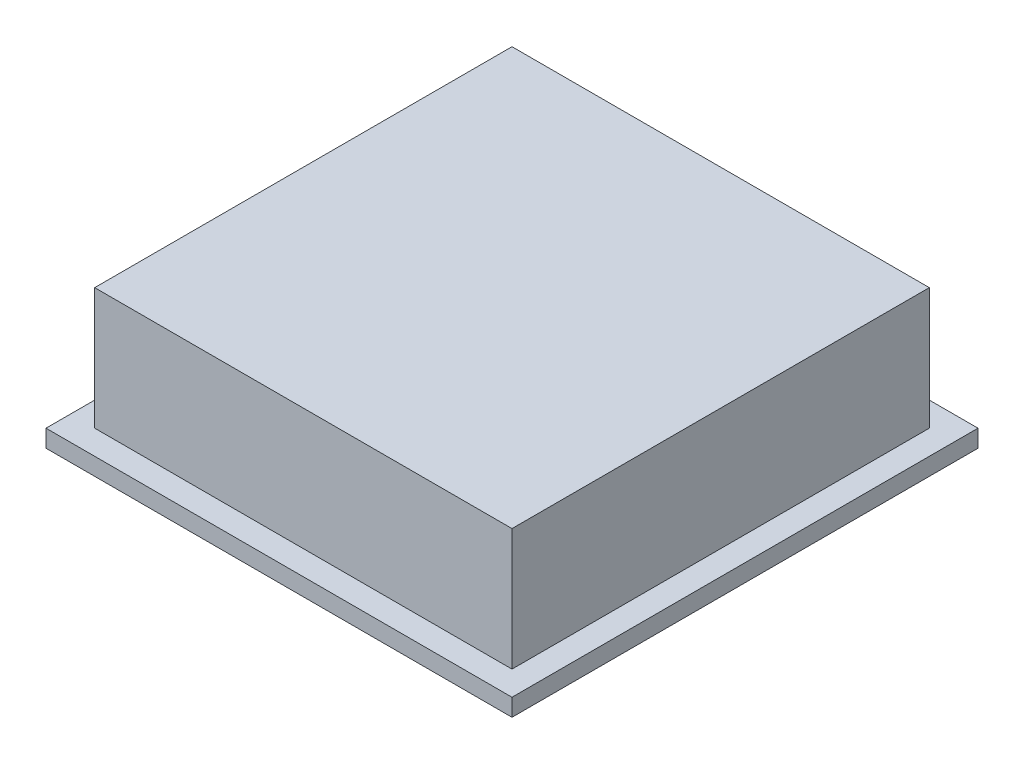
SolidWorks part; units mm, degrees
ref_plane "Front" through (0, 0, 0) normal (0, 0, 1) x (1, 0, 0)
ref_plane "Top" through (0, 0, 0) normal (0, 1, 0) x (1, 0, 0)
ref_plane "Right" through (0, 0, 0) normal (1, 0, 0) x (0, 0, -1)
sketch "Sketch3" plane through (0, 0, 0) normal (0, 1, 0) x (1, 0, 0)
  line L1 (-6.7, -6.7) -> (6.7, -6.7)
  line L2 (-6.7, -6.7) -> (-6.7, 6.7)
  line L3 (-6.7, 6.7) -> (6.7, 6.7)
  line L4 (6.7, -6.7) -> (6.7, 6.7)
  line L5 (-6.7, -6.7) -> (6.7, 6.7) construction
  line L6 (-6.7, 6.7) -> (6.7, -6.7) construction
  point P0 (0, 0)
  dimension "D1" = 13.4
  dimension "D2" = 13.4
extrude "Boss-Extrude2" add sketch "Sketch3" along normal blind 0.5
sketch "Sketch4" plane through (0, 0, 0) normal (0, 1, 0) x (1, 0, 0)
  line L1 (-6, -6) -> (6, -6)
  line L2 (-6, -6) -> (-6, 6)
  line L3 (-6, 6) -> (6, 6)
  line L4 (6, -6) -> (6, 6)
  line L5 (-6, -6) -> (6, 6) construction
  line L6 (-6, 6) -> (6, -6) construction
  point P0 (0, 0)
  dimension "D1" = 12
  dimension "D2" = 12
extrude "Boss-Extrude3" add sketch "Sketch4" along normal blind 4
